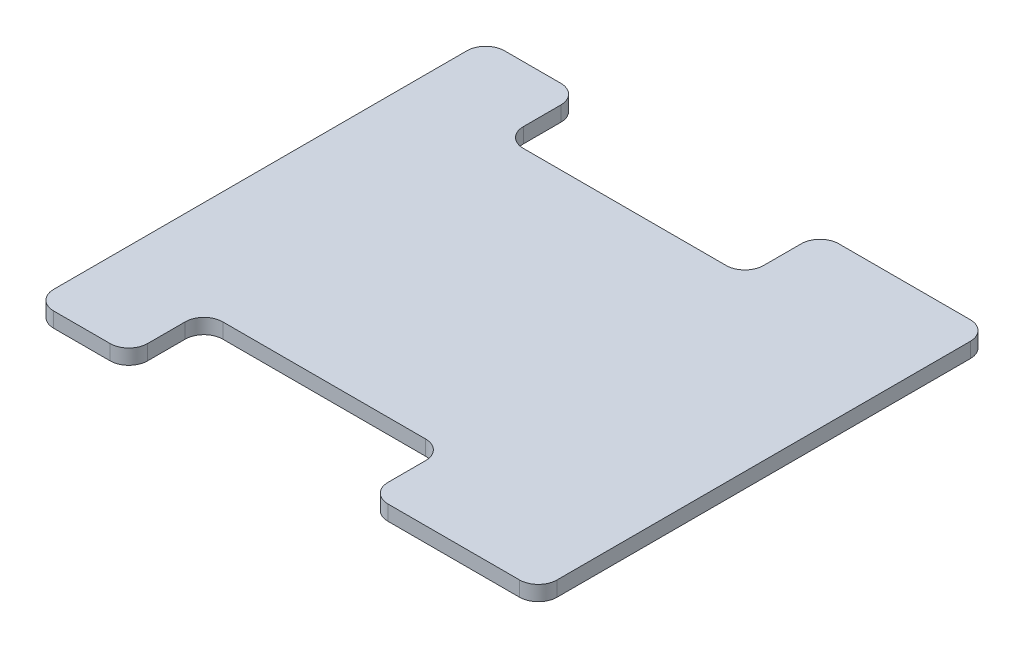
SolidWorks part; units mm, degrees
ref_plane "Plano frontal" through (0, 0, 0) normal (0, 0, 1) x (1, 0, 0)
ref_plane "Plano superior" through (0, 0, 0) normal (0, 1, 0) x (1, 0, 0)
ref_plane "Plano direito" through (0, 0, 0) normal (1, 0, 0) x (0, 0, -1)
sketch "Esboço1" plane through (0, 0, 0) normal (0, 1, 0) x (1, 0, 0)
  line L0 (-47, -60) -> (-62, -60)
  line L1 (62, 60) -> (27, 60)
  line L2 (67, 55) -> (67, -55)
  line L3 (62, -60) -> (27, -60)
  line L4 (-67, 55) -> (-67, -55)
  line L5 (67, 60) -> (-67, -60) construction
  line L6 (67, -60) -> (-67, 60) construction
  line L8 (-42, 55) -> (-42, 45)
  line L9 (-37, 40) -> (17, 40)
  line L10 (22, 55) -> (22, 45)
  line L11 (-47, 60) -> (-62, 60)
  line L12 (-42, -55) -> (-42, -45)
  line L13 (-37, -40) -> (17, -40)
  line L14 (22, -55) -> (22, -45)
  arc A0 (67, -55) -> (62, -60) centre (62, -55) cw
  arc A1 (62, 60) -> (67, 55) centre (62, 55) cw
  arc A2 (27, -60) -> (22, -55) centre (27, -55) cw
  arc A3 (27, 60) -> (22, 55) centre (27, 55) ccw
  arc A4 (-47, 60) -> (-42, 55) centre (-47, 55) cw
  arc A5 (-42, 45) -> (-37, 40) centre (-37, 45) ccw
  arc A6 (17, 40) -> (22, 45) centre (17, 45) ccw
  arc A7 (17, -40) -> (22, -45) centre (17, -45) cw
  arc A8 (-42, -45) -> (-37, -40) centre (-37, -45) cw
  arc A9 (-47, -60) -> (-42, -55) centre (-47, -55) ccw
  arc A10 (-62, -60) -> (-67, -55) centre (-62, -55) cw
  arc A11 (-62, 60) -> (-67, 55) centre (-62, 55) ccw
  point P0 (0, 0)
  point P23 (22, -60)
  point P28 (-42, 60)
  point P31 (-42, 40)
  point P34 (22, 40)
  point P37 (22, -40)
  point P40 (-42, -40)
  point P43 (-42, -60)
  dimension "D9" = 5
  dimension "D1" = 120
  dimension "D2" = 35
  dimension "D3" = 20
  dimension "D4" = 20
  dimension "D5" = 64
  dimension "D6" = 64
  dimension "D7" = 25
  dimension "D8" = 25
extrude "Ressalto-extrusão1" add sketch "Esboço1" along normal blind 4
